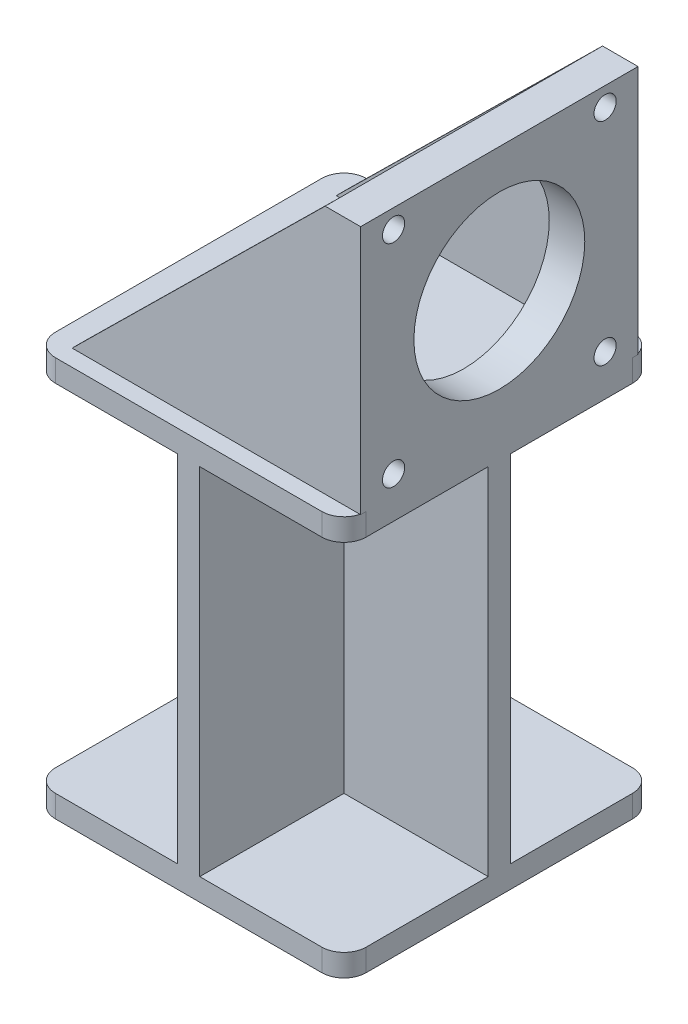
SolidWorks part; units mm, degrees
ref_plane "Front Plane" through (0, 0, 0) normal (0, 0, 1) x (1, 0, 0)
ref_plane "Top Plane" through (0, 0, 0) normal (0, 1, 0) x (1, 0, 0)
ref_plane "Right Plane" through (0, 0, 0) normal (1, 0, 0) x (0, 0, -1)
sketch "Sketch2" plane through (0, 0, 0) normal (0, 1, 0) x (1, 0, 0)
  line L1 (-30, -35) -> (30, -35)
  line L2 (-35, -30) -> (-35, 30)
  line L3 (-30, 35) -> (30, 35)
  line L4 (35, -30) -> (35, 30)
  line L5 (-35, -35) -> (35, 35) construction
  line L6 (-35, 35) -> (35, -35) construction
  arc A0 (30, 35) -> (35, 30) centre (30, 30) cw
  arc A1 (30, -35) -> (35, -30) centre (30, -30) ccw
  arc A2 (-35, -30) -> (-30, -35) centre (-30, -30) ccw
  arc A3 (-30, 35) -> (-35, 30) centre (-30, 30) ccw
  point P0 (0, 0)
  dimension "D3" = 5
  dimension "D1" = 70
  dimension "D2" = 70
extrude "Boss-Extrude1" add sketch "Sketch2" along normal blind 5
sketch "Sketch3" plane through (0, 5, 0) normal (0, 1, 0) x (1, 0, 0)
  line L0 (0, 35) -> (0, -35) construction
  line L1 (30, 35) -> (-30, 35) construction
  line L2 (-30, -35) -> (30, -35) construction
  line L3 (-35, 0) -> (35, 0) construction
  line L4 (-35, 30) -> (-35, -30) construction
  line L5 (35, -30) -> (35, 30) construction
  line L6 (-2.5, 2.5) -> (-2.5, 35)
  line L7 (2.5, -35) -> (-2.5, -35)
  line L8 (2.5, -35) -> (2.5, -2.5)
  line L9 (2.5, 35) -> (-2.5, 35)
  line L10 (-2.5, -35) -> (-2.5, -2.5)
  line L11 (2.5, -35) -> (-2.5, 35) construction
  line L12 (2.5, 35) -> (-2.5, -35) construction
  line L13 (35, -2.5) -> (2.5, -2.5)
  line L14 (35, -2.5) -> (35, 2.5)
  line L15 (35, 2.5) -> (2.5, 2.5)
  line L16 (-35, -2.5) -> (-35, 2.5)
  line L17 (35, -2.5) -> (-35, 2.5) construction
  line L18 (35, 2.5) -> (-35, -2.5) construction
  line L19 (-2.5, 2.5) -> (-35, 2.5)
  line L21 (2.5, 2.5) -> (2.5, 35)
  line L24 (-2.5, -2.5) -> (-35, -2.5)
  point P12 (0, 0)
  point P17 (0, 0)
  dimension "D1" = 5
  dimension "D2" = 5
extrude "Boss-Extrude2" add sketch "Sketch3" along normal blind 80
ref_plane "Plane1" through (0, 45, 0) normal (0, 1, 0) x (1, 0, 0)
mirror "Mirror1" about plane through (0, 45, 0) normal (0, 1, 0) of "Boss-Extrude1"
sketch "Sketch4" plane through (35, 0, 0) normal (1, 0, 0) x (0, 0, -1)
  line L3 (-28.25, 90) -> (28.25, 90)
  line L5 (-28.25, 146.2) -> (28.25, 90) construction
  line L6 (-28.25, 90) -> (28.25, 146.2) construction
  line L7 (0, 133.6259) -> (0, 101.6067) construction
  line L9 (-28.25, 146.2) -> (28.25, 146.2)
  line L10 (-28.25, 90) -> (-28.25, 146.2)
  line L11 (28.25, 146.2) -> (28.25, 90)
  line L12 (-23.8295, 141.9295) -> (0, 118.1) construction
  line L13 (0, 118.1) -> (-25.4302, 118.1) construction
  line L14 (-30, 90) -> (30, 90) construction
  circle A0 centre (0, 118.1) radius 19.25
  circle A3 centre (-23.8295, 141.9295) radius 2.5
  circle A4 centre (23.8295, 141.9295) radius 2.5
  circle A5 centre (23.8295, 94.2705) radius 2.5
  circle A6 centre (-23.8295, 94.2705) radius 2.5
  point P0 (0, 118.1)
  dimension "D4" = 38.5
  dimension "D5" = 33.7
  dimension "D7" = 5
  dimension "D1" = 56.2
  dimension "D6" = 45
extrude "Boss-Extrude3" add sketch "Sketch4" against normal blind 8
sketch "Sketch5" plane through (0, 0, 28.25) normal (0, 0, 1) x (1, 0, 0)
  line L3 (35, 90) -> (-30, 90)
  line L4 (-30, 90) -> (27, 146.2)
  line L5 (27, 146.2) -> (35, 146.2)
  line L6 (35, 146.2) -> (35, 90)
extrude "Boss-Extrude4" add sketch "Sketch5" along normal blind 3
ref_plane "Plane2" through (0, 0, 0) normal (0, 0, -1) x (-1, 0, 0)
mirror "Mirror2" about plane through (0, 0, 0) normal (0, 0, -1) of "Boss-Extrude4"
